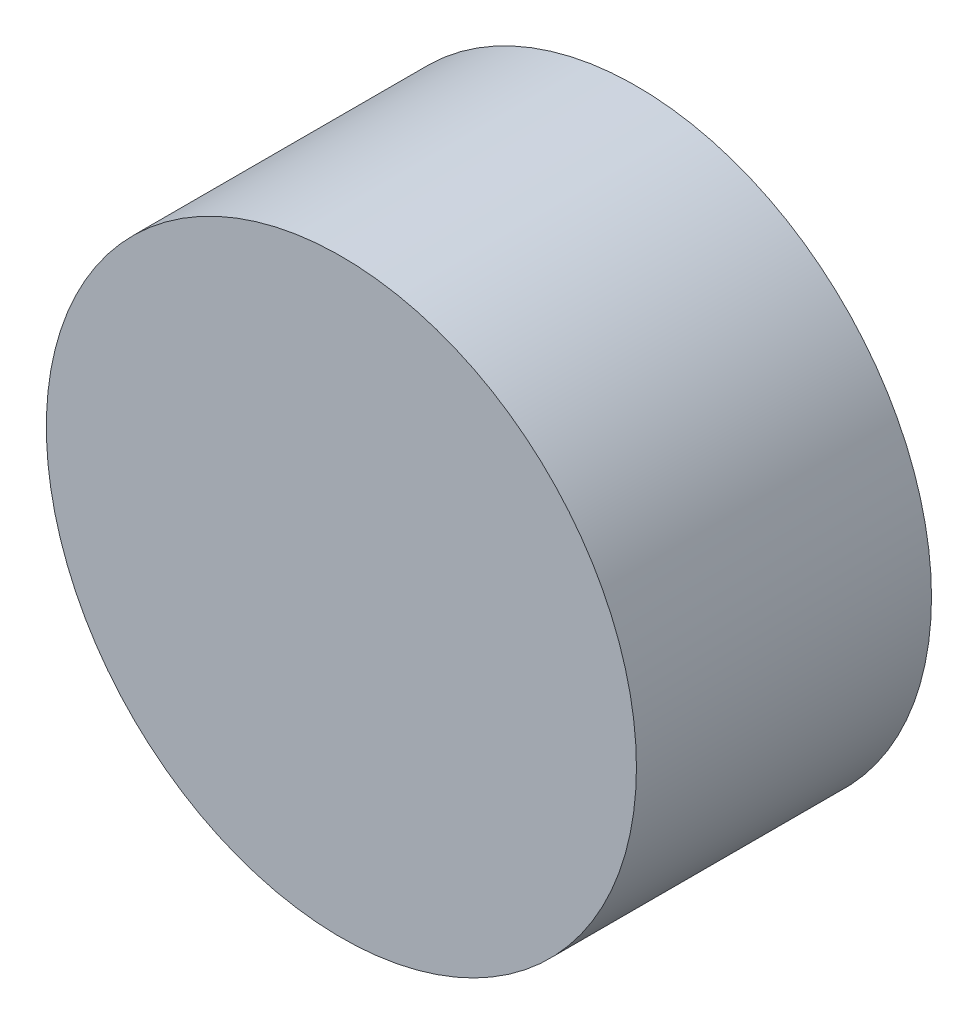
SolidWorks part; units mm, degrees
ref_plane "Front Plane" through (0, 0, 0) normal (0, 0, 1) x (1, 0, 0)
ref_plane "Top Plane" through (0, 0, 0) normal (0, 1, 0) x (1, 0, 0)
ref_plane "Right Plane" through (0, 0, 0) normal (1, 0, 0) x (0, 0, -1)
sketch "Sketch1" plane through (0, 0, 0) normal (0, 0, 1) x (1, 0, 0)
  circle A0 centre (0, 0) radius 25.4
  dimension "D1" = 50.8
extrude "Boss-Extrude2" add sketch "Sketch1" along normal blind 25.4
